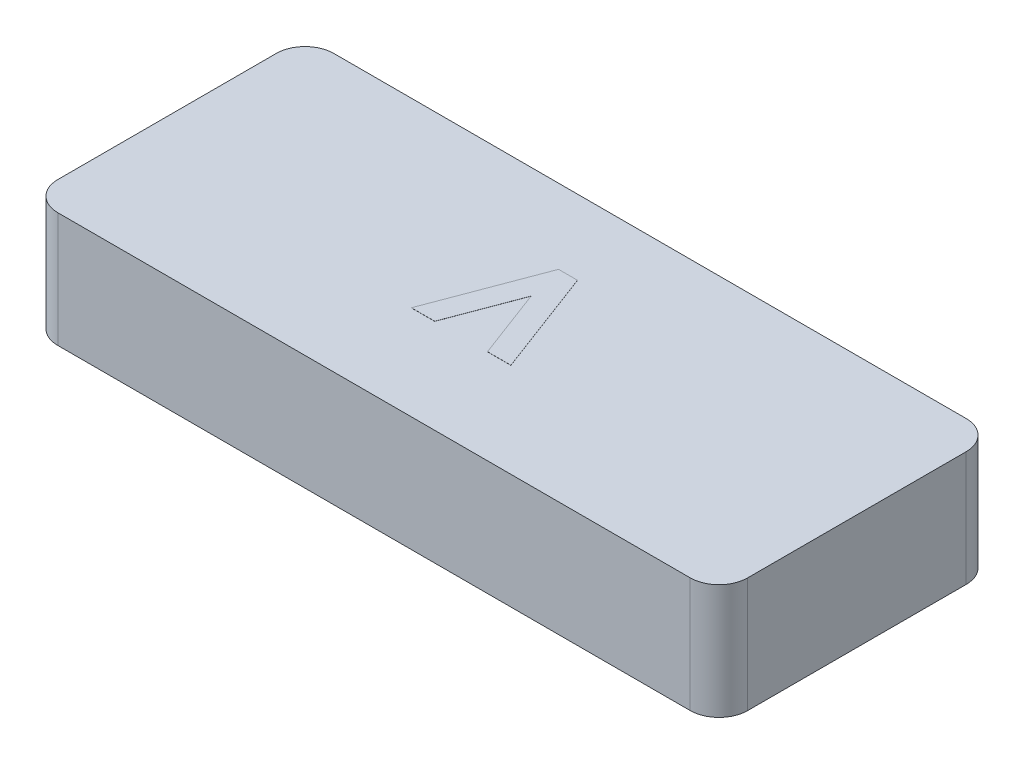
SolidWorks part; units mm, degrees
ref_plane "Front Plane" through (0, 0, 0) normal (0, 0, 1) x (1, 0, 0)
ref_plane "Top Plane" through (0, 0, 0) normal (0, 1, 0) x (1, 0, 0)
ref_plane "Right Plane" through (0, 0, 0) normal (1, 0, 0) x (0, 0, -1)
sketch "Sketch1" plane through (0, 0, 0) normal (0, 1, 0) x (1, 0, 0)
  line L0 (0, 0) -> (0, 6.096)
  line L1 (0, -54.9123) -> (0, 54.9123) construction
  line L2 (0, 6.096) -> (15.24, 6.096)
  line L3 (15.24, 6.096) -> (15.24, 0)
  line L4 (-55, 0) -> (55, 0) construction
  line L5 (15.24, 0) -> (0, 0)
  dimension "D1" = 15.24
  dimension "D2" = 6.096
extrude "Boss-Extrude1" add sketch "Sketch1" along normal blind 2.54 contours L2 L3 L5 L0
shell "Shell1" thickness 0.635
fillet "Fillet1" radius 0.635 4 edges at (15.24, 1.27, -6.096) (15.24, 1.27, 0) (0, 1.27, -6.096) (0, 1.27, 0)
sketch "Sketch2" plane through (0, 1.905, 0) normal (0, -1, 0) x (1, 0, 0)
  line L0 (14.605, -0.635) -> (0.635, -0.635) construction
  line L2 (7.62, -0.635) -> (7.62, -5.461) construction
  line L3 (0.635, -5.461) -> (14.605, -5.461) construction
  line L4 (0.635, -3.048) -> (14.605, -3.048) construction
  line L5 (0.635, -0.635) -> (0.635, -5.461) construction
  line L6 (14.605, -5.461) -> (14.605, -0.635) construction
  circle A0 centre (7.62, -3.048) radius 1.5875
  dimension "D1" = 3.175
extrude "Boss-Extrude2" add sketch "Sketch2" along normal up to surface (1.905 mm away) up to face at (7.62, 0, -3.048)
sketch "Sketch3" plane through (0, 2.54, 0) normal (0, 1, 0) x (1, 0, 0)
  line L0 (0, 0.635) -> (0, 5.461) construction
  line L1 (0.635, 6.096) -> (14.605, 6.096) construction
  text T0 "<b>^</b>"
  dimension "D1" = 6.096
  dimension "D2" = 4.826
extrude "Boss-Extrude3" add sketch "Sketch3" along normal blind 0.0025
